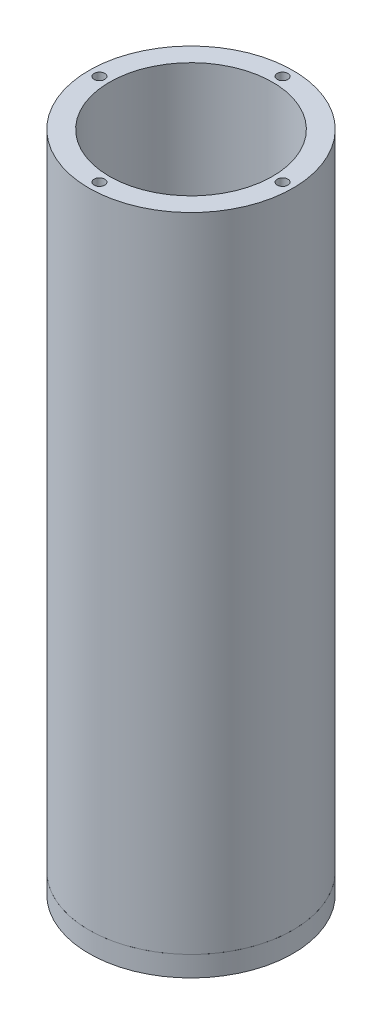
SolidWorks part; units mm, degrees
ref_plane "Front Plane" through (0, 0, 0) normal (0, 0, 1) x (1, 0, 0)
ref_plane "Top Plane" through (0, 0, 0) normal (0, 1, 0) x (1, 0, 0)
ref_plane "Right Plane" through (0, 0, 0) normal (1, 0, 0) x (0, 0, -1)
sketch "Sketch1" plane through (0, 0, 0) normal (0, 1, 0) x (1, 0, 0)
  circle A0 centre (0, 0) radius 25.4
  circle A1 centre (0, 0) radius 31.75
  circle A2 centre (0, 0) radius 25 construction
  dimension "D1" = 50.8
  dimension "D2" = 50
  dimension "D3" = 63.5
extrude "Boss-Extrude1" add sketch "Sketch1" along normal blind 200
sketch "Sketch2" plane through (0, 0, 0) normal (0, -1, 0) x (1, 0, 0)
  circle A0 centre (0, 0) radius 31.75 construction
  circle A1 centre (0, 0) radius 31.75
extrude "Boss-Extrude2" add sketch "Sketch2" along normal blind 6.35 separate body
hole_wizard "M4x0.7 Tapped Hole1" positions "Sketch4" profile "Sketch3" tap size "M4x0.7" standard "ANSI Metric"
sketch "Sketch4" plane through (0, 200, 0) normal (0, 1, 0) x (1, 0, 0)
  circle A0 centre (0, 0) radius 28.5 construction
  point P5 (0, 28.5)
  point P7 (28.5, 0)
  point P9 (0, -28.5)
  point P11 (-28.5, 0)
  dimension "D1" = 57
cosmetic thread "Hole Thread1"
cosmetic thread "Hole Thread2"
cosmetic thread "Hole Thread3"
cosmetic thread "Hole Thread4"
sketch "Sketch3" plane through (0, 200, -28.5) normal (1, 0, 0) x (0, 0, 1)
  line L0 (0, 0) -> (0, 11.0914)
  line L1 (0, 11.0914) -> (1.65, 10.1)
  line L2 (1.65, 10.1) -> (1.65, 0)
  line L5 (1.65, 0) -> (0, 0)
  line L10 (0, 11.0914) -> (-1.65, 10.1) construction
  line L11 (0, -6.35) -> (0, 107.95) construction
  dimension "Tap Drill Dia." = 3.3
  dimension "Tap Drill Depth" = 10.1
  dimension "Drill Angle" = 118
